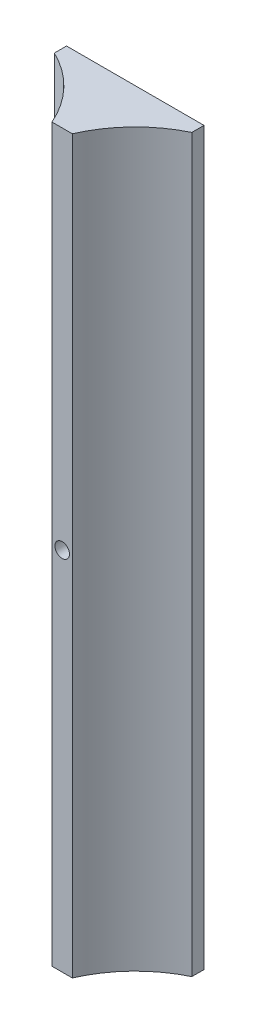
SolidWorks part; units mm, degrees
ref_plane "Front" through (0, 0, 0) normal (0, 0, 1) x (1, 0, 0)
ref_plane "Top" through (0, 0, 0) normal (0, 1, 0) x (1, 0, 0)
ref_plane "Right" through (0, 0, 0) normal (1, 0, 0) x (0, 0, -1)
sketch "Sketch1" plane through (0, 0, 0) normal (0, 1, 0) x (1, 0, 0)
  line L0 (-0.8348, 0) -> (0.8348, 0)
  line L1 (5.6411, 5) -> (5.6411, 6)
  line L2 (5.6411, 6) -> (-5.6411, 6)
  line L3 (-5.6411, 6) -> (-5.6411, 5)
  arc A0 (0.8348, 0) -> (5.6411, 5) centre (10, -4) cw
  arc A1 (-5.6411, 5) -> (-0.8348, 0) centre (-10, -4) cw
  point P9 (0, 6)
  point P10 (0, 0)
  dimension "D1" = 10
  dimension "D6" = 6
  dimension "D2" = 20
  dimension "D3" = 10
  dimension "D4" = 1
extrude "Boss-Extrude1" add sketch "Sketch1" along normal blind 60
sketch "Sketch3" plane through (0, 0, -6) normal (0, 0, -1) x (-1, 0, 0)
  line L0 (0, 0) -> (0, 60) construction
  line L1 (-5.6411, 0) -> (5.6411, 0) construction
  line L2 (-5.6411, 60) -> (5.6411, 60) construction
  point P6 (0, 30)
  point P8 (0, 0)
  dimension "D2" = 30
hole_wizard "Tapped Hole for M2.5x0.45 Helicoil1" positions "3DSketch1" profile "Sketch4" tap size "M2.5x0.45" standard "Helicoil® Metric"
sketch3d "3DSketch1"
  point P0 (0, 30, -6)
  point P7 (0, 0, 0)
cosmetic thread "Hole Thread2" parameters "D1"=3, "D2"=3.145
sketch "Sketch4" plane through (0, 30, -6) normal (1, 0, 0) x (0, 1, 0)
  line L0 (0, 0) -> (0, 4.7661)
  line L1 (0, 4.7661) -> (1.275, 4)
  line L2 (1.275, 4) -> (1.275, 0)
  line L5 (1.275, 0) -> (0, 0)
  line L10 (0, 4.7661) -> (-1.275, 4) construction
  line L11 (0, -6.35) -> (0, 107.95) construction
  dimension "Tap Drill Dia." = 2.55
  dimension "Tap Drill Depth" = 4
  dimension "Drill Angle" = 118
hole_wizard "Ø1.2 (1.2) Diameter Hole1" positions "3DSketch2" profile "Sketch5" hole size "Ø1.2" standard "ANSI Metric"
sketch3d "3DSketch2"
  point P0 (0, 30, -6)
  point P7 (0, 0, 0)
sketch "Sketch5" plane through (0, 30, -6) normal (1, 0, 0) x (0, 1, 0)
  line L0 (0, 0) -> (0, 6.8105)
  line L1 (0, 6.8105) -> (0.6, 6.45)
  line L2 (0.6, 6.45) -> (0.6, 0)
  line L5 (0.6, 0) -> (0, 0)
  line L10 (0, 6.8105) -> (-0.6, 6.45) construction
  line L11 (0, -6.35) -> (0, 107.95) construction
  dimension "Hole Dia." = 1.2
  dimension "Hole Depth" = 6.45
  dimension "Drill Angle" = 118
